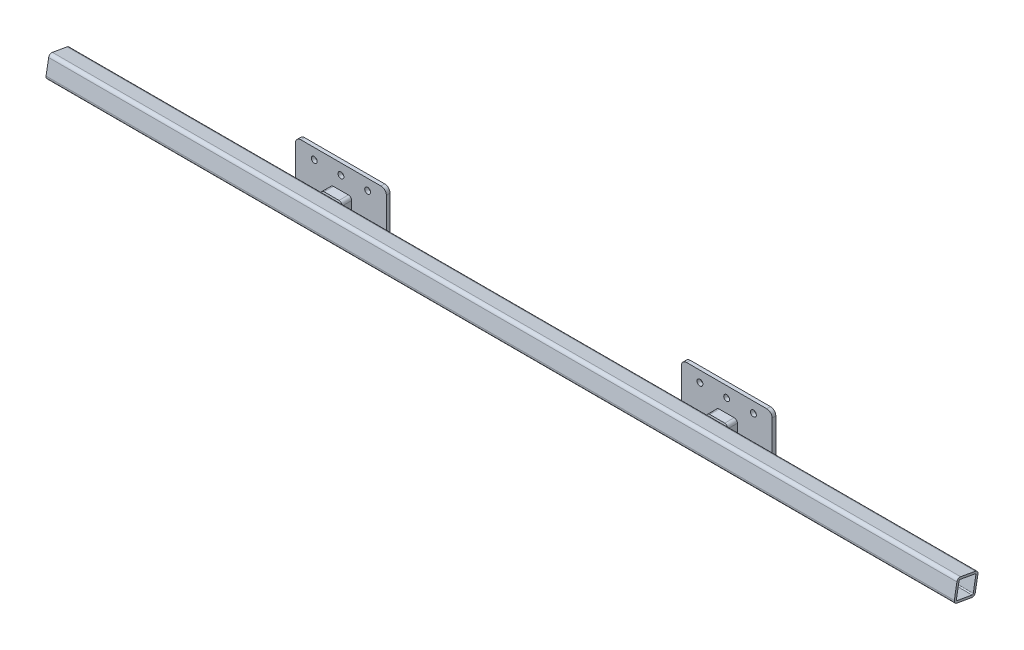
SolidWorks part; units mm, degrees
material "1.0037 (S235JR)"
ref_plane "Płaszczyzna przednia" through (0, 0, 0) normal (0, 0, 1) x (1, 0, 0)
ref_plane "Płaszczyzna górna" through (0, 0, 0) normal (0, 1, 0) x (1, 0, 0)
ref_plane "Płaszczyzna prawa" through (0, 0, 0) normal (1, 0, 0) x (0, 0, -1)
sketch "Szkic1" plane through (0, 0, 0) normal (0, 0, 1) x (1, 0, 0)
  line L0 (0, 70.851) -> (0, -151.9204) construction
  line L1 (-436, 0) -> (-286, 0)
  line L2 (-446, 10) -> (-446, 80)
  line L3 (-436, 90) -> (-286, 90)
  line L4 (-276, 10) -> (-276, 80)
  line L5 (276, 10) -> (276, 80)
  line L6 (436, 90) -> (286, 90)
  line L7 (446, 10) -> (446, 80)
  line L8 (436, 0) -> (286, 0)
  circle A0 centre (-411, 70) radius 5.5
  circle A1 centre (-361, 70) radius 5.5
  circle A2 centre (-311, 70) radius 5.5
  arc A3 (-446, 80) -> (-436, 90) centre (-436, 80) cw
  arc A4 (-286, 90) -> (-276, 80) centre (-286, 80) cw
  arc A5 (-286, 0) -> (-276, 10) centre (-286, 10) ccw
  arc A6 (-436, 0) -> (-446, 10) centre (-436, 10) cw
  arc A7 (436, 0) -> (446, 10) centre (436, 10) ccw
  arc A8 (286, 0) -> (276, 10) centre (286, 10) cw
  arc A9 (286, 90) -> (276, 80) centre (286, 80) ccw
  arc A10 (446, 80) -> (436, 90) centre (436, 80) ccw
  circle A11 centre (311, 70) radius 5.5
  circle A12 centre (361, 70) radius 5.5
  circle A13 centre (411, 70) radius 5.5
  point P15 (-361, 90)
  point P18 (-446, 90)
  point P21 (-276, 90)
  point P24 (-276, 0)
  point P27 (-446, 0)
  point P46 (446, 0)
  point P47 (276, 0)
  point P48 (276, 90)
  point P49 (446, 90)
  dimension "D4" = 11
  dimension "D8" = 10
  dimension "D1" = 622
  dimension "D2" = 170
  dimension "D3" = 90
  dimension "D5" = 20
  dimension "D6" = 50
  dimension "D7" = 50
extrude "Dodanie-wyciągnięcie1" add sketch "Szkic1" along normal blind 5 and the other way blind 2
sketch "Szkic2" plane through (0, 0, 0) normal (1, 0, 0) x (0, 0, -1)
  line L0 (-28.5438, 45.4342) -> (-56.1184, 50.2963)
  line L1 (-63.0691, 45.4294) -> (-67.9313, 17.8548)
  line L2 (-63.0643, 10.904) -> (-35.4897, 6.0419)
  line L3 (-28.5389, 10.9088) -> (-23.6768, 38.4835)
  line L4 (-5, 10) -> (-5, 80) construction
  line L5 (-43.9188, 7.5282) -> (-29.5808, 5) construction
  line L6 (-29.2383, 41.495) -> (-56.813, 46.3571)
  line L7 (-59.1299, 44.7348) -> (-63.992, 17.1602)
  line L8 (-62.3697, 14.8433) -> (-34.7951, 9.9811)
  line L9 (-32.4782, 11.6034) -> (-27.616, 39.1781)
  line L10 (-27.4319, 17.1869) -> (-29.5808, 5) construction
  arc A0 (-67.9313, 17.8548) -> (-63.0643, 10.904) centre (-62.0224, 16.8129) ccw
  arc A1 (-35.4897, 6.0419) -> (-28.5389, 10.9088) centre (-34.4478, 11.9507) ccw
  arc A2 (-56.1184, 50.2963) -> (-63.0691, 45.4294) centre (-57.1603, 44.3875) ccw
  arc A3 (-28.5438, 45.4342) -> (-23.6768, 38.4835) centre (-29.5856, 39.5254) cw
  arc A4 (-56.813, 46.3571) -> (-59.1299, 44.7348) centre (-57.1603, 44.3875) ccw
  arc A5 (-63.992, 17.1602) -> (-62.3697, 14.8433) centre (-62.0224, 16.8129) ccw
  arc A6 (-34.7951, 9.9811) -> (-32.4782, 11.6034) centre (-34.4478, 11.9507) ccw
  arc A7 (-29.2383, 41.495) -> (-27.616, 39.1781) centre (-29.5856, 39.5254) cw
  point P11 (-68.9731, 11.9459)
  point P16 (-62.0272, 51.3382)
  point P19 (-22.6349, 44.3923)
  dimension "D5" = 6
  dimension "D1" = 10
  dimension "D2" = 40
  dimension "D3" = 40
  dimension "D4" = 70
  dimension "D7" = 5
  dimension "D6" = 4
extrude "Dodanie-wyciągnięcie2" add sketch "Szkic2" along normal blind 850 and the other way blind 850 separate body
sketch "Szkic3" plane through (0, 0, 5) normal (0, 0, -1) x (-1, 0, 0)
  line L0 (375, 45) -> (347, 45)
  line L1 (341, 39) -> (341, 11)
  line L2 (347, 5) -> (375, 5)
  line L3 (381, 11) -> (381, 39)
  line L4 (436, 0) -> (286, 0) construction
  line L5 (286, 90) -> (436, 90) construction
  line L6 (375, 41) -> (347, 41)
  line L7 (345, 39) -> (345, 11)
  line L8 (347, 9) -> (375, 9)
  line L9 (377, 11) -> (377, 39)
  line L10 (0, 90.6997) -> (0, -66.5042) construction
  line L11 (-377, 11) -> (-377, 39)
  line L12 (-347, 9) -> (-375, 9)
  line L13 (-345, 39) -> (-345, 11)
  line L14 (-375, 41) -> (-347, 41)
  line L15 (-381, 11) -> (-381, 39)
  line L16 (-347, 5) -> (-375, 5)
  line L17 (-341, 39) -> (-341, 11)
  line L18 (-375, 45) -> (-347, 45)
  arc A0 (341, 11) -> (347, 5) centre (347, 11) ccw
  arc A1 (375, 5) -> (381, 11) centre (375, 11) ccw
  arc A2 (347, 45) -> (341, 39) centre (347, 39) ccw
  arc A3 (375, 45) -> (381, 39) centre (375, 39) cw
  arc A4 (347, 41) -> (345, 39) centre (347, 39) ccw
  arc A5 (345, 11) -> (347, 9) centre (347, 11) ccw
  arc A6 (375, 9) -> (377, 11) centre (375, 11) ccw
  arc A7 (375, 41) -> (377, 39) centre (375, 39) cw
  arc A8 (-375, 41) -> (-377, 39) centre (-375, 39) ccw
  arc A9 (-375, 9) -> (-377, 11) centre (-375, 11) cw
  arc A10 (-345, 11) -> (-347, 9) centre (-347, 11) cw
  arc A11 (-347, 41) -> (-345, 39) centre (-347, 39) cw
  arc A12 (-375, 45) -> (-381, 39) centre (-375, 39) ccw
  arc A13 (-347, 45) -> (-341, 39) centre (-347, 39) cw
  arc A14 (-375, 5) -> (-381, 11) centre (-375, 11) cw
  arc A15 (-341, 11) -> (-347, 5) centre (-347, 11) cw
  point P14 (361, 45)
  point P17 (361, 90)
  dimension "D4" = 6
  dimension "D1" = 40
  dimension "D2" = 5
  dimension "D3" = 40
  dimension "D5" = 4
extrude "Dodanie-wyciągnięcie3" add sketch "Szkic3" against normal up to surface (18.5857 mm away) separate body
hole_wizard "Otwór gwintowany M101" positions "Szkic4" profile "Szkic5" tap size "M10" standard "ISO"
sketch "Szkic4" plane through (0, -0.2094, 0.0369) normal (0, -0.9848, 0.1736) x (-1, 0, 0)
  line L0 (850, -63.9997) -> (850, -35.9997) construction
  line L1 (-850, -63.9997) -> (-850, -35.9997) construction
  point P0 (800, -49.9997)
  point P6 (850, -49.9997)
  point P7 (-800, -49.9997)
  point P12 (0, 0)
  point P13 (-850, -49.9997)
  dimension "D1" = 50
  dimension "D2" = 50
sketch "Szkic5" plane through (-800, 8.473, 49.277) normal (1, 0, 0) x (0, -0.1736, -0.9848)
  line L0 (0, 0) -> (0, 30.0537)
  line L1 (0, 30.0537) -> (4.25, 27.5)
  line L2 (4.25, 27.5) -> (4.25, 0)
  line L5 (4.25, 0) -> (0, 0)
  line L10 (0, 30.0537) -> (-4.25, 27.5) construction
  line L11 (0, -6.35) -> (0, 107.95) construction
  dimension "Średnica wiertła gwintu" = 8.5
  dimension "Głębokość otworu gwintowanego" = 27.5
  dimension "Kąt wiertła" = 118
cosmetic thread "Gwint otworu1" parameters "D1"=5, "D2"=10
cosmetic thread "Gwint otworu2" parameters "D1"=5, "D2"=10
